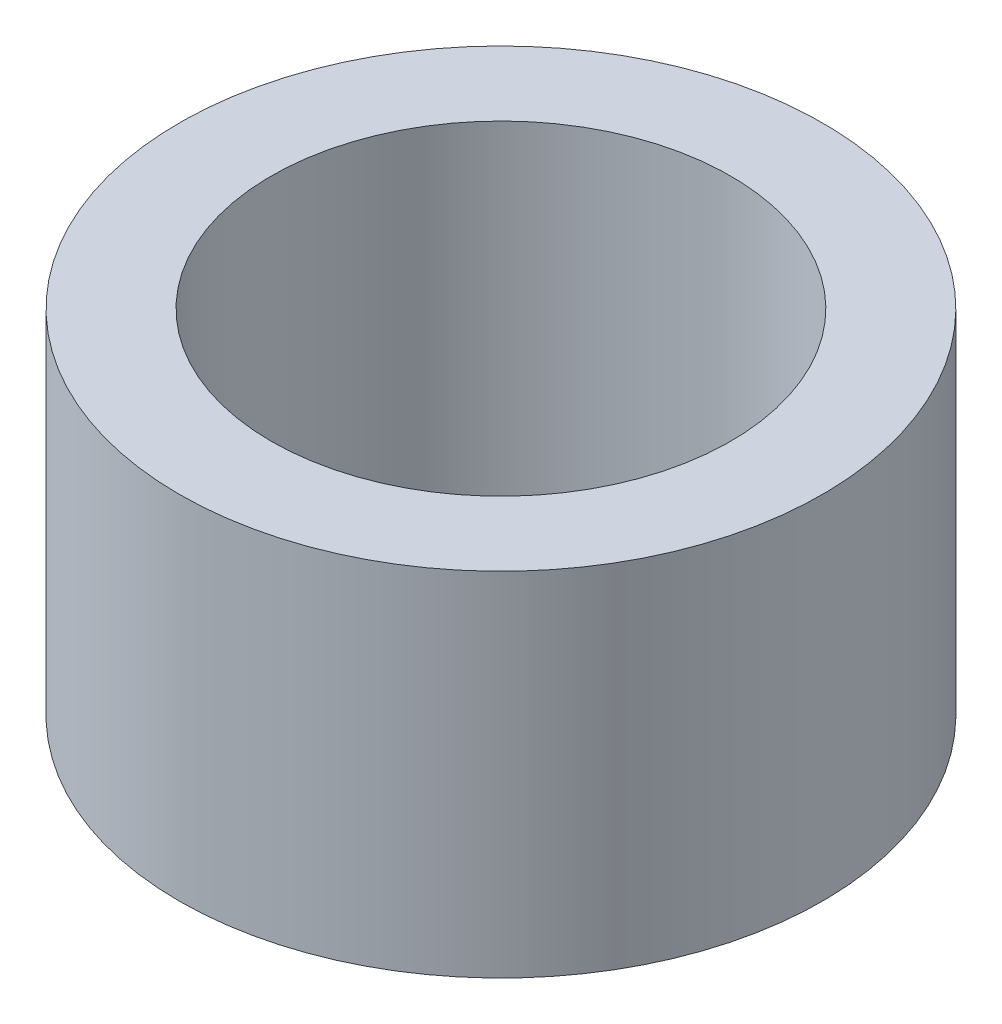
SolidWorks part; units mm, degrees
ref_plane "正面" through (0, 0, 0) normal (0, 0, 1) x (1, 0, 0)
ref_plane "平面" through (0, 0, 0) normal (0, 1, 0) x (1, 0, 0)
ref_plane "右側面" through (0, 0, 0) normal (1, 0, 0) x (0, 0, -1)
sketch "ｽｹｯﾁ1" plane through (0, 0, 0) normal (0, 1, 0) x (1, 0, 0)
  circle A0 centre (0, 0) radius 3
  circle A1 centre (0, 0) radius 4.2
  dimension "D1" = 6
  dimension "D2" = 1.2
extrude "ﾎﾞｽ - 押し出し1" add sketch "ｽｹｯﾁ1" along normal blind 4.6
sketch "ｽｹｯﾁ3" plane through (0, 4.6, 0) normal (0, 1, 0) x (1, 0, 0)
  circle A1 centre (0, 0) radius 4.2
  circle A2 centre (0, 0) radius 4.2
  dimension "D1" = 0
